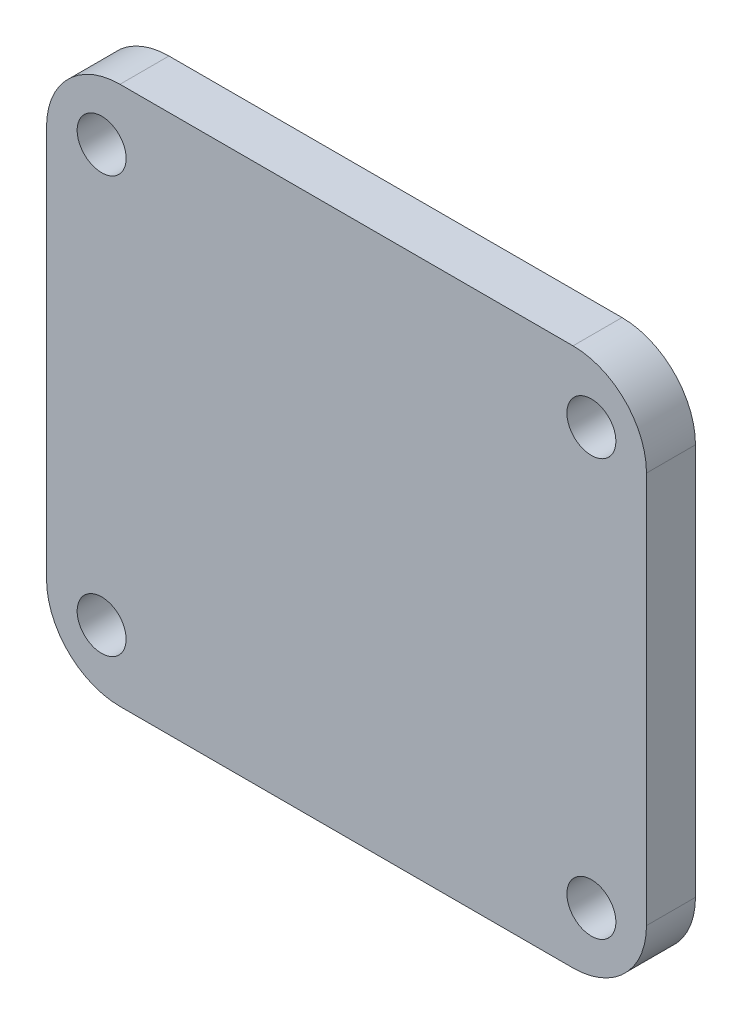
SolidWorks part; units mm, degrees
ref_plane "Piano frontale" through (0, 0, 0) normal (0, 0, 1) x (1, 0, 0)
ref_plane "Piano superiore" through (0, 0, 0) normal (0, 1, 0) x (1, 0, 0)
ref_plane "Piano destro" through (0, 0, 0) normal (1, 0, 0) x (0, 0, -1)
sketch "Schizzo1" plane through (0, 0, 0) normal (0, 0, 1) x (1, 0, 0)
  line L0 (20, 0) -> (0, 17) construction
  line L2 (-2.25, -2.5019) -> (22.25, -2.5019)
  line L3 (-2.25, -2.5019) -> (-2.25, 19.5019)
  line L4 (-2.25, 19.5019) -> (22.25, 19.5019)
  line L5 (22.25, -2.5019) -> (22.25, 19.5019)
  line L6 (-2.25, -2.5019) -> (22.25, 19.5019) construction
  line L7 (-2.25, 19.5019) -> (22.25, -2.5019) construction
  circle A0 centre (0, 0) radius 1
  circle A1 centre (20, 0) radius 1
  circle A2 centre (20, 17) radius 1
  circle A3 centre (0, 17) radius 1
  point P9 (10, 8.5)
  point P14 (-2.25, 19.5019)
  point P16 (0, 0)
  point P17 (0, 0)
  dimension "D1" = 2
  dimension "D2" = 20
  dimension "D3" = 17
  dimension "D4" = 24.5
  dimension "D5" = 22.0038
extrude "Estrusione-Estrusione1" add sketch "Schizzo1" along normal blind 2
fillet "Raccordo1" radius 3 4 edges at (22.25, -2.5019, 1) (-2.25, -2.5019, 1) (22.25, 19.5019, 1) (-2.25, 19.5019, 1)
